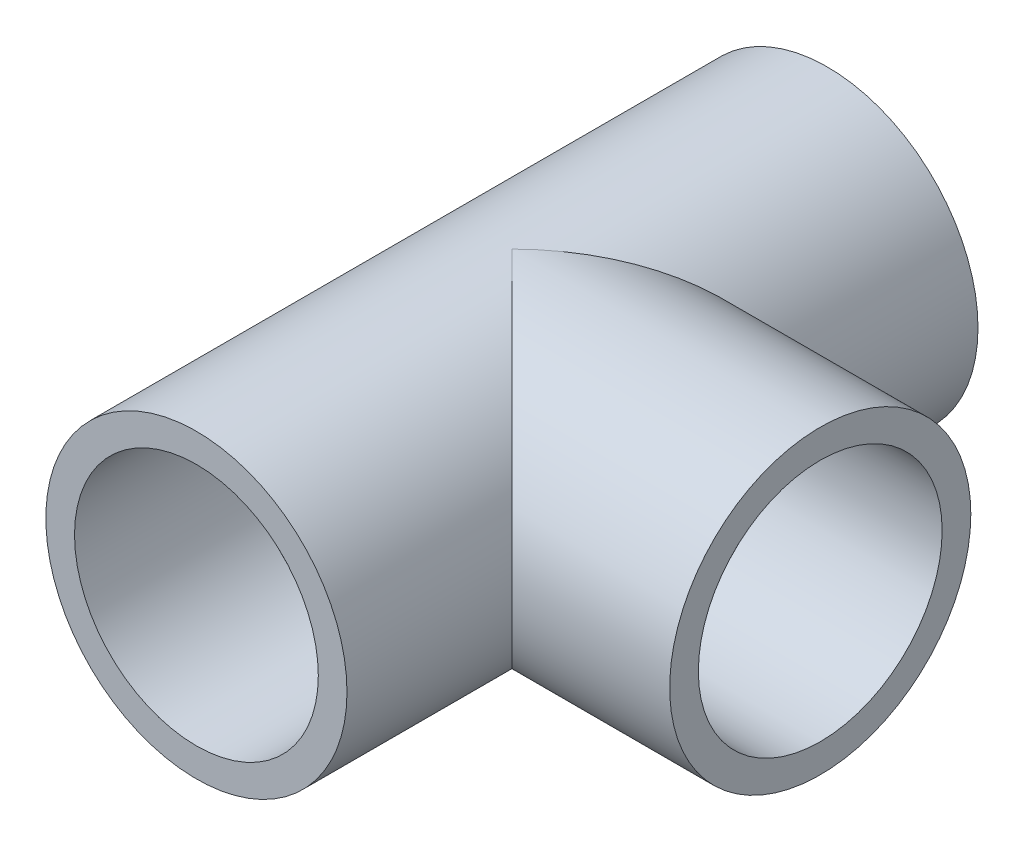
SolidWorks part; units mm, degrees
ref_plane "Front Plane" through (0, 0, 0) normal (0, 0, 1) x (1, 0, 0)
ref_plane "Top Plane" through (0, 0, 0) normal (0, 1, 0) x (1, 0, 0)
ref_plane "Right Plane" through (0, 0, 0) normal (1, 0, 0) x (0, 0, -1)
sketch "Sketch1" plane through (0, 0, 0) normal (0, 0, 1) x (1, 0, 0)
  circle A0 centre (0, 0) radius 16.6687
  dimension "D1" = 33.3375
extrude "Boss-Extrude1" add sketch "Sketch1" along normal blind 69.85
sketch "Sketch2" plane through (0, 0, 0) normal (1, 0, 0) x (0, 0, -1)
  line L0 (0, -16.6687) -> (0, 16.6687) construction
  circle A0 centre (-34.925, 0) radius 16.6687
  dimension "D1" = 34.925
  dimension "D2" = 33.3375
extrude "Boss-Extrude2" add sketch "Sketch2" along normal blind 34.1313
sketch "Sketch3" plane through (34.1313, 0, 0) normal (1, 0, 0) x (0, 0, -1)
  circle A0 centre (-34.925, 0) radius 12.7
  dimension "D1" = 25.4
extrude "Cut-Extrude1" cut sketch "Sketch3" against normal blind 30.48
sketch "Sketch5" plane through (0, 0, 0) normal (0, 0, -1) x (-1, 0, 0)
  circle A0 centre (0, 0) radius 12.7
  dimension "D1" = 25.4
extrude "Cut-Extrude3" cut sketch "Sketch5" against normal through all
sketch "Sketch7" plane through (0, 0, 69.85) normal (0, 0, 1) x (1, 0, 0)
  circle A0 centre (0, 0) radius 13.4938
  dimension "D1" = 26.9875
extrude "Cut-Extrude4" cut sketch "Sketch7" against normal blind 19.05
sketch "Sketch8" plane through (34.1313, 0, 0) normal (1, 0, 0) x (0, 0, -1)
  circle A0 centre (-34.925, 0) radius 13.4937
  dimension "D1" = 26.9875
extrude "Cut-Extrude5" cut sketch "Sketch8" against normal blind 19.05
sketch "Sketch9" plane through (0, 0, 0) normal (0, 0, -1) x (-1, 0, 0)
  circle A0 centre (0, 0) radius 13.4938
  dimension "D1" = 26.9875
extrude "Cut-Extrude6" cut sketch "Sketch9" against normal blind 19.05
